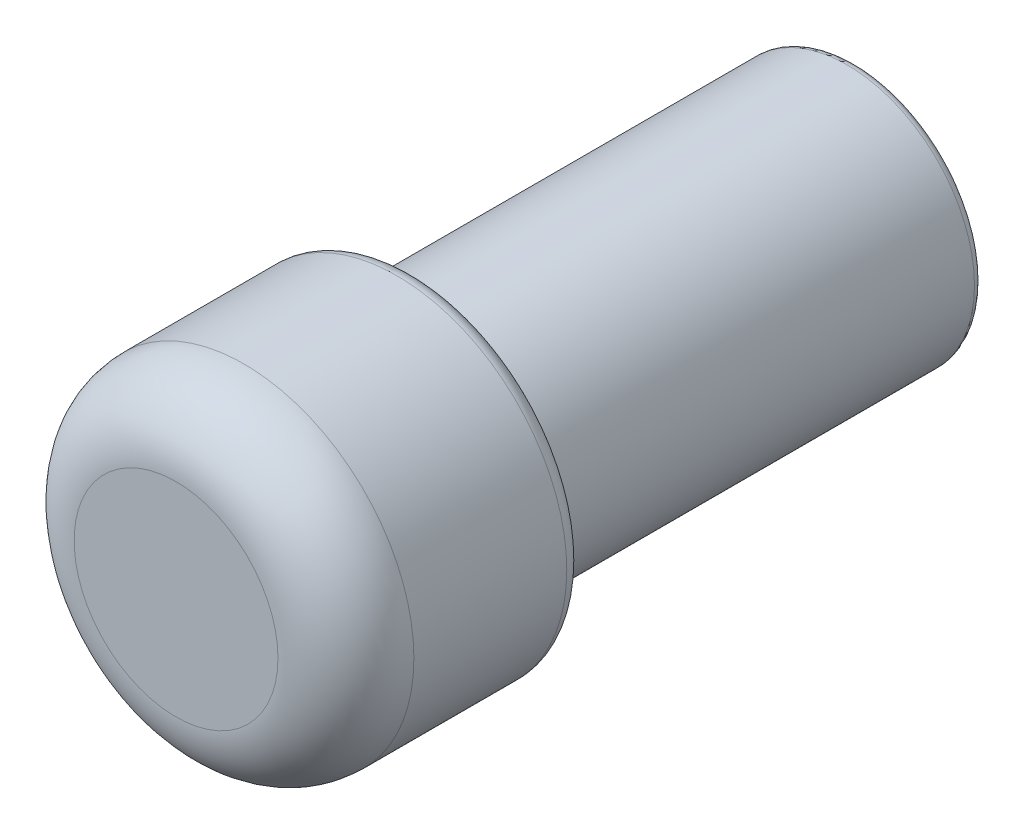
SolidWorks part; units mm, degrees
ref_plane "Front Plane" through (0, 0, 0) normal (0, 0, 1) x (1, 0, 0)
ref_plane "Top Plane" through (0, 0, 0) normal (0, 1, 0) x (1, 0, 0)
ref_plane "Right Plane" through (0, 0, 0) normal (1, 0, 0) x (0, 0, -1)
sketch "Sketch1" plane through (0, 0, 0) normal (0, 0, 1) x (1, 0, 0)
  circle A0 centre (0, 0) radius 3.75
  dimension "D1" = 7.5
extrude "Boss-Extrude1" add sketch "Sketch1" along normal blind 13 contours A0
sketch "Sketch2" plane through (0, 0, 13) normal (0, 0, 1) x (1, 0, 0)
  circle A0 centre (0, 0) radius 5
  dimension "D1" = 10
extrude "Boss-Extrude2" add sketch "Sketch2" along normal blind 7
sketch "Sketch3" plane through (0, 0, 0) normal (0, 0, -1) x (-1, 0, 0)
  circle A0 centre (0, 0) radius 2.85
  dimension "D1" = 5.7
extrude "Cut-Extrude1" cut sketch "Sketch3" against normal blind 15
fillet "Fillet1" radius 0.5 2 edges at (5, 0, 13) (3.75, 0, 13)
fillet "Fillet2" radius 0.25 2 edges at (3.75, 0, 0) (-2.85, 0, 0)
fillet "Fillet3" radius 2 1 edges at (5, 0, 20)
